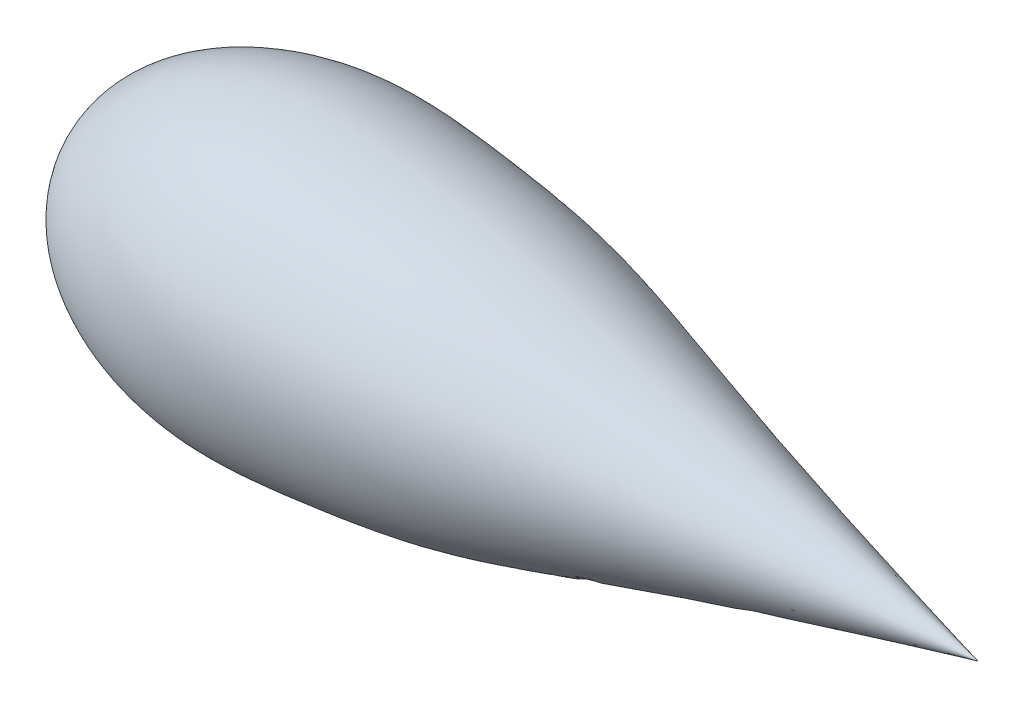
SolidWorks part; units mm, degrees
ref_plane "Alzado" through (0, 0, 0) normal (1, 0, 0) x (0, 1, 0)
ref_plane "Planta" through (0, 0, 0) normal (0, 0, 1) x (0, 1, 0)
ref_plane "Vista lateral" through (0, 0, 0) normal (0, 1, 0) x (-1, 0, 0)
sketch "Croquis1" plane through (0, 0, 0) normal (0, 0, 1) x (0, 1, 0)
  line L0 (0, 302.5112) -> (0, -897.4888) construction
  line L1 (0, 302.5112) -> (0, 2.5112) construction
  line L2 (0, 2.5112) -> (200, 2.5112) construction
  line L3 (-65.4246, 302.5112) -> (65.4246, 302.5112) construction
  line L4 (200, 213.8561) -> (200, -5.8755) construction
  line L5 (0, 302.5112) -> (0, -897.4888)
  spline S0 degree 3 poles (0, -897.4888) (145.504, -302.7753) (170.7849, -369.666) (213.6539, 124.8285) (118.7591, 302.5112) (0, 302.5112) knots 0 0 0 0 0.639219 0.739219 1 1 1 1
  point P3 (0, 0)
  point P4 (0, 0)
  dimension "D3" = 1200
  dimension "D1" = 300
  dimension "D2" = 200
revolve "Revolución1" add sketch "Croquis1" angle 360 about L5
scale "Escala1" scale about centroid uniform scaling yes scale factor 0.7
